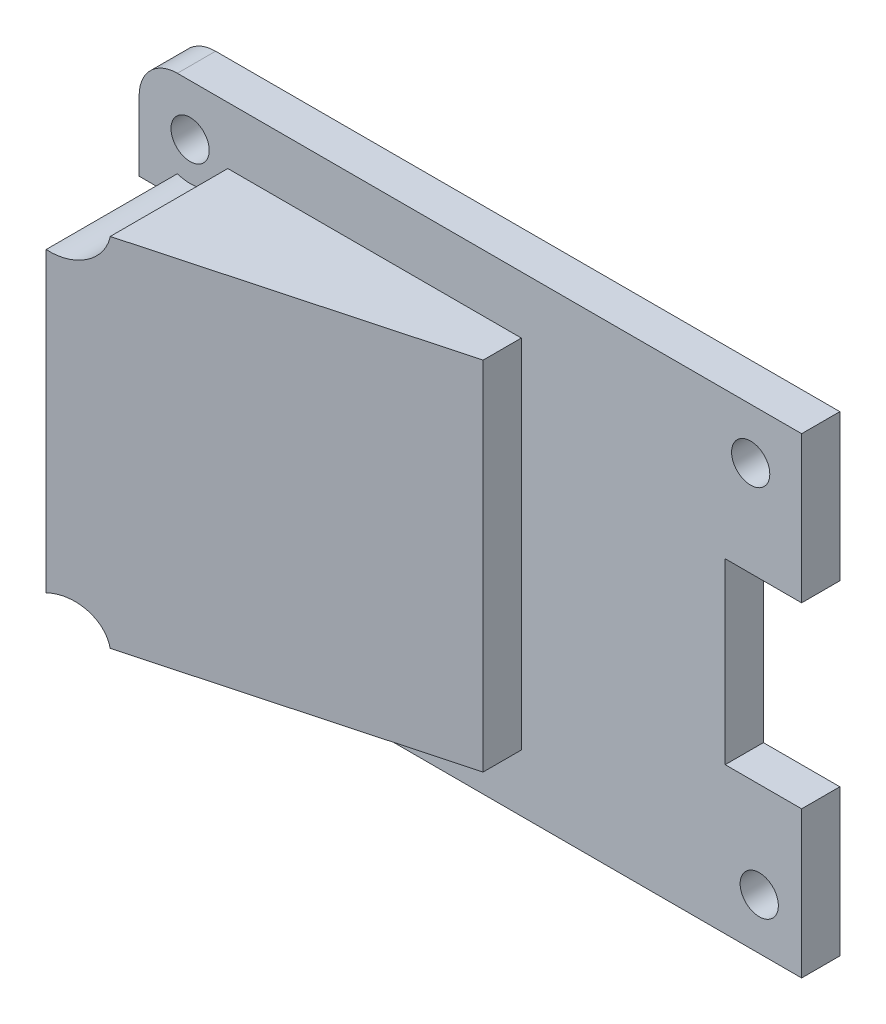
SolidWorks part; units mm, degrees
ref_plane "Alzado" through (0, 0, 0) normal (0, 0, 1) x (1, 0, 0)
ref_plane "Planta" through (0, 0, 0) normal (0, 1, 0) x (1, 0, 0)
ref_plane "Vista lateral" through (0, 0, 0) normal (1, 0, 0) x (0, 0, -1)
sketch "Croquis1" plane through (0, 0, 0) normal (0, 0, 1) x (1, 0, 0)
  line L1 (-65.2968, 25.2877) -> (-13.2968, 25.2877)
  line L2 (-65.2968, 25.2877) -> (-65.2968, -11.7123)
  line L3 (-65.2968, -11.7123) -> (-13.2968, -11.7123)
  line L4 (-13.2968, 25.2877) -> (-13.2968, -11.7123)
  dimension "D1" = 52
  dimension "D2" = 37
extrude "Saliente-Extruir1" add sketch "Croquis1" along normal blind 3
fillet "Redondeo1" radius 3 2 edges at (-65.2968, -11.7123, 1.5) (-65.2968, 25.2877, 1.5)
sketch "Croquis2" plane through (0, 0, 3) normal (0, 0, 1) x (1, 0, 0)
  line L0 (-62.2968, -11.7123) -> (-13.2968, -11.7123) construction
  line L3 (-65.2968, 22.2877) -> (-65.2968, -8.7123) construction
  circle A0 centre (-61.2968, 21.2877) radius 1.5
  circle A1 centre (-61.2968, -7.7123) radius 1.5
  circle A2 centre (-16.6241, -7.7123) radius 1.5
  circle A3 centre (-17.2968, 21.2877) radius 1.5
  dimension "D1" = 29
  dimension "D4" = 29
  dimension "D2" = 4
  dimension "D3" = 4
  dimension "D5" = 44
  dimension "D6" = 4
extrude "Cortar-Extruir1" cut sketch "Croquis2" against normal blind 3
sketch "Croquis3" plane through (0, 0, 3) normal (0, 0, 1) x (1, 0, 0)
  line L0 (-65.2968, 22.2877) -> (-65.2968, -8.7123) construction
  line L1 (-65.2968, 16.7877) -> (-36.2968, 16.7877)
  line L2 (-65.2968, 16.7877) -> (-65.2968, -3.2123)
  line L3 (-65.2968, -3.2123) -> (-36.2968, -3.2123)
  line L4 (-36.2968, 16.7877) -> (-36.2968, -3.2123)
  line L5 (-62.2968, -11.7123) -> (-13.2968, -11.7123) construction
  line L7 (-13.2968, -11.7123) -> (-13.2968, 25.2877) construction
  line L9 (-13.2968, 13.7877) -> (-19.2968, 13.7877)
  line L10 (-13.2968, 13.7877) -> (-13.2968, -0.2123)
  line L11 (-13.2968, -0.2123) -> (-19.2968, -0.2123)
  line L12 (-19.2968, 13.7877) -> (-19.2968, -0.2123)
  dimension "D1" = 29
  dimension "D2" = 20
  dimension "D3" = 8.5
  dimension "D4" = 6
  dimension "D5" = 14
  dimension "D6" = 11.5
extrude "Cortar-Extruir2" cut sketch "Croquis3" against normal blind 3
sketch "Croquis4" plane through (0, 0, 3) normal (0, 0, 1) x (1, 0, 0)
  line L0 (-57.2968, 16.7877) -> (-57.2968, 20.7902)
  line L1 (-36.2968, 16.7877) -> (-65.2968, 16.7877) construction
  line L2 (-57.2968, 20.7902) -> (-26.2968, 20.7902)
  line L3 (-26.2968, 20.7902) -> (-26.2968, -7.2123)
  line L4 (-26.2968, -7.2123) -> (-57.2968, -7.2123)
  line L5 (-57.2968, -7.2123) -> (-57.2968, -3.2123)
  line L6 (-65.2968, -3.2123) -> (-36.2968, -3.2123) construction
  line L7 (-57.2968, -3.2123) -> (-36.2968, -3.2123)
  line L8 (-36.2968, -3.2123) -> (-36.2968, 16.7877)
  line L9 (-36.2968, 16.7877) -> (-57.2968, 16.7877)
  line L10 (-65.2968, 22.2877) -> (-65.2968, 16.7877) construction
  line L11 (-65.2968, -3.2123) -> (-65.2968, -8.7123) construction
  dimension "D1" = 4
  dimension "D2" = 10
  dimension "D3" = 4.0026
  dimension "D4" = 8
  dimension "D5" = 8
extrude "Saliente-Extruir2" add sketch "Croquis4" along normal blind 9
sketch "Croquis5" plane through (0, 0, 12) normal (0, 0, 1) x (1, 0, 0)
  line L1 (-26.2968, 20.7902) -> (-62.2968, 20.7902)
  line L2 (-26.2968, 20.7902) -> (-26.2968, -7.2123)
  line L3 (-26.2968, -7.2123) -> (-62.2968, -7.2123)
  line L4 (-62.2968, 20.7902) -> (-62.2968, -7.2123)
  dimension "D1" = 28.0026
  dimension "D2" = 36
extrude "Saliente-Extruir3" add sketch "Croquis5" along normal blind 10.3
sketch "Croquis6" plane through (0, -7.2123, 0) normal (0, -1, 0) x (1, 0, 0)
  line L0 (-35.2968, 15) -> (-35.2968, 12.9954)
  line L2 (-35.2968, 12.9954) -> (-26.2968, 12.9954)
  line L3 (-35.2968, 15) -> (-62.2968, 22.3)
  line L6 (-26.2968, 22.3) -> (-26.2968, 3) construction
  line L7 (-26.2968, 14.7574) -> (-26.2968, 22.3)
  line L8 (-26.2968, 22.3) -> (-62.2968, 22.3)
  line L9 (-26.2968, 12.9954) -> (-26.2968, 14.7574)
extrude "Cortar-Extruir3" cut sketch "Croquis6" against normal up to vertex
sketch "Croquis7" plane through (1.3749, 0, 5.0851) normal (0.261, 0, 0.9653) x (0.9653, 0, -0.261)
  line L0 (-65.9578, 6.7889) -> (-65.9578, -26.7111)
  line L1 (-65.9578, 20.7902) -> (-65.9578, -7.2123) construction
  line L2 (-65.9578, -26.7111) -> (-37.9578, -26.7111)
  line L3 (-37.9578, -26.7111) -> (-37.9578, 40.2889)
  line L4 (-37.9578, 40.2889) -> (-65.9578, 40.2889)
  line L5 (-65.9578, 40.2889) -> (-65.9578, 6.7889)
  dimension "D1" = 28
  dimension "D2" = 67
  dimension "D3" = 33.5
  dimension "D4" = 33.5
extrude "Saliente-Extruir4" add sketch "Croquis7" along normal blind 8.5
sketch "Croquis8" plane through (3.5933, 0, 13.2905) normal (0.261, 0, 0.9653) x (0.9653, 0, -0.261)
  line L0 (-65.9578, -26.7111) -> (-37.9578, -26.7111) construction
  line L1 (-62.9078, -23.6611) -> (-41.0078, -23.6611)
  line L2 (-62.9078, -23.6611) -> (-62.9078, 37.2389)
  line L3 (-62.9078, 37.2389) -> (-41.0078, 37.2389)
  line L4 (-41.0078, -23.6611) -> (-41.0078, 37.2389)
  line L5 (-37.9578, 40.2889) -> (-65.9578, 40.2889) construction
  line L6 (-65.9578, 40.2889) -> (-65.9578, -26.7111) construction
  line L7 (-37.9578, -26.7111) -> (-37.9578, 40.2889) construction
  dimension "D1" = 3.05
  dimension "D2" = 3.05
  dimension "D3" = 3.05
  dimension "D4" = 3.05
extrude "Cortar-Extruir4" cut sketch "Croquis8" against normal blind 5.5
sketch "Croquis10" plane through (0, 20.7902, 0) normal (0, 1, 0) x (1, 0, 0)
  line L0 (-62.2968, -22.3) -> (-35.2968, -15)
  line L1 (-35.2968, -15) -> (-35.2968, -12)
  line L2 (-35.2968, -12) -> (-62.2968, -19.3)
  line L3 (-62.2968, -22.3) -> (-62.2968, -12) construction
  line L4 (-62.2968, -19.3) -> (-62.2968, -22.3)
extrude "Cortar-Extruir5" cut sketch "Croquis10" against normal blind 9
sketch "Croquis12" plane through (0, 20.7902, 0) normal (0, 1, 0) x (1, 0, 0)
  line L0 (-26.2968, -12.9954) -> (-35.2968, -12.9954)
  line L1 (-26.2968, -12.9954) -> (-26.2968, -11.4245)
  line L2 (-26.2968, -12.9954) -> (-26.2968, -3) construction
  line L4 (-26.2968, -11.4245) -> (-35.2968, -11.4245)
  line L5 (-35.2968, -11.4245) -> (-35.2968, -12.9954)
extrude "Cortar-Extruir6" cut sketch "Croquis12" against normal up to vertex
sketch "Croquis13" plane through (3.5933, 0, 13.2905) normal (0.261, 0, 0.9653) x (0.9653, 0, -0.261)
  line L0 (-37.9578, 40.2889) -> (-65.9578, 40.2889) construction
  line L1 (-37.9578, -26.7111) -> (-40.9578, -26.7111)
  line L2 (-37.9578, -26.7111) -> (-37.9578, 40.2889)
  line L3 (-37.9578, 40.2889) -> (-40.9578, 40.2889)
  line L4 (-40.9578, -26.7111) -> (-40.9578, 40.2889)
extrude "Saliente-Extruir5" add sketch "Croquis13" along normal blind 12
sketch "Croquis14" plane through (0, -7.2123, 0) normal (0, -1, 0) x (1, 0, 0)
  line L1 (-57.2968, 12) -> (-26.2968, 12)
  line L2 (-57.2968, 12) -> (-57.2968, 3)
  line L3 (-57.2968, 3) -> (-26.2968, 3)
  line L4 (-26.2968, 12) -> (-26.2968, 3)
extrude "Cortar-Extruir7" cut sketch "Croquis14" against normal up to vertex
sketch "Croquis17" plane through (0, 0, 3) normal (0, 0, 1) x (1, 0, 0)
  line L0 (-13.2968, -0.2123) -> (-19.2968, -0.2123)
  line L1 (-19.2968, -0.2123) -> (-19.2968, 13.7877)
  line L2 (-19.2968, 13.7877) -> (-13.2968, 13.7877)
  line L3 (-13.2968, 13.7877) -> (-13.2968, 25.2877)
  line L4 (-13.2968, 25.2877) -> (-62.2968, 25.2877)
  line L5 (-65.2968, 22.2877) -> (-65.2968, 16.7877)
  line L7 (-65.2968, 16.7877) -> (-36.2968, 16.7877)
  line L8 (-36.2968, 16.7877) -> (-36.2968, -3.2123)
  line L9 (-36.2968, -3.2123) -> (-65.2968, -3.2123)
  line L10 (-65.2968, -3.2123) -> (-65.2968, -8.7123)
  line L11 (-62.2968, -11.7123) -> (-13.2968, -11.7123)
  line L12 (-13.2968, -11.7123) -> (-13.2968, -0.2123)
  arc A0 (-62.2968, -11.7123) -> (-65.2968, -8.7123) centre (-62.2968, -8.7123) cw
  arc A1 (-65.2968, 22.2877) -> (-62.2968, 25.2877) centre (-62.2968, 22.2877) cw
  circle A2 centre (-61.2968, 21.2877) radius 1.5
  circle A3 centre (-61.2968, -7.7123) radius 1.5
  circle A4 centre (-16.6241, -7.7123) radius 1.5
  circle A5 centre (-17.2968, 21.2877) radius 1.5
extrude "Saliente-Extruir6" add sketch "Croquis17" along normal up to vertex (9 mm away)
sketch "Croquis18" plane through (0, -11.7123, 0) normal (0, -1, 0) x (1, 0, 0)
  line L1 (-13.2968, 0) -> (-67.494, 0)
  line L2 (-13.2968, 0) -> (-13.2968, 9)
  line L3 (-13.2968, 9) -> (-67.494, 9)
  line L4 (-67.494, 0) -> (-67.494, 9)
  dimension "D1" = 9
extrude "Cortar-Extruir8" cut sketch "Croquis18" against normal up to vertex
sketch "Croquis19" plane through (0, 0, 9) normal (0, 0, -1) x (-1, 0, 0)
  circle A0 centre (61.2968, 21.2877) radius 1.5
  circle A1 centre (61.2968, -7.7123) radius 1.5
extrude "Cortar-Extruir9" cut sketch "Croquis19" against normal up to vertex
sketch "Croquis20" plane through (1.3749, 0, 5.0851) normal (-0.261, 0, -0.9653) x (-0.9653, 0, 0.261)
  line L0 (37.9578, -26.7111) -> (37.9578, 40.2889) construction
  line L1 (65.9578, 40.2889) -> (37.9578, 40.2889)
  line L2 (65.9578, 40.2889) -> (65.9578, 34.2889)
  line L3 (65.9578, 34.2889) -> (37.9578, 34.2889)
  line L4 (37.9578, 40.2889) -> (37.9578, 34.2889)
  dimension "D1" = 6
extrude "Saliente-Extruir7" add sketch "Croquis20" along normal blind 3
sketch "Croquis21" plane through (0, 0, 9) normal (0, 0, -1) x (-1, 0, 0)
  line L0 (65.2968, 16.7877) -> (36.2968, 16.7877) construction
  line L1 (55.2968, 16.7877) -> (35.2968, 16.7877)
  line L2 (55.2968, 16.7877) -> (55.2968, 21.2877)
  line L3 (55.2968, 21.2877) -> (35.2968, 21.2877)
  line L4 (35.2968, 16.7877) -> (35.2968, 21.2877)
  line L5 (36.2968, -3.2123) -> (65.2968, -3.2123) construction
  line L6 (55.2968, -3.2123) -> (35.2968, -3.2123)
  line L7 (55.2968, -3.2123) -> (55.2968, -7.7123)
  line L8 (55.2968, -7.7123) -> (35.2968, -7.7123)
  line L9 (35.2968, -3.2123) -> (35.2968, -7.7123)
  line L10 (13.2968, 25.2877) -> (62.2968, 25.2877) construction
  line L11 (13.2968, -11.7123) -> (62.2968, -11.7123) construction
  line L12 (65.2968, 22.2877) -> (65.2968, 16.7877) construction
  line L13 (65.2968, -3.2123) -> (65.2968, -8.7123) construction
  dimension "D1" = 4
  dimension "D2" = 4
  dimension "D3" = 10
  dimension "D4" = 10
  dimension "D5" = 20
  dimension "D6" = 20
extrude "Cortar-Extruir10" cut sketch "Croquis21" against normal blind 2
sketch "Croquis22" plane through (0, 0, 12) normal (0, 0, 1) x (1, 0, 0)
  circle A0 centre (-61.2968, 21.2877) radius 3
  circle A1 centre (-61.2968, -7.7123) radius 3
extrude "Cortar-Extruir11" cut sketch "Croquis22" along normal up to vertex (10.3 mm away)
sketch "Croquis23" plane through (0, 0, 12) normal (0, 0, 1) x (1, 0, 0)
  circle A0 centre (-61.2968, 21.2877) radius 2
  circle A1 centre (-61.2968, -7.7123) radius 2
extrude "Cortar-Extruir12" cut sketch "Croquis23" along normal up to vertex
sketch "Croquis24" plane through (1.3749, 0, 5.0851) normal (-0.261, 0, -0.9653) x (-0.9653, 0, 0.261)
  line L1 (37.9578, -26.7111) -> (69.5992, -26.7111)
  line L2 (37.9578, -26.7111) -> (37.9578, 48.9096)
  line L3 (37.9578, 48.9096) -> (69.5992, 48.9096)
  line L4 (69.5992, -26.7111) -> (69.5992, 48.9096)
extrude "Cortar-Extruir13" cut sketch "Croquis24" against normal up to vertex
sketch "Croquis25" plane through (0.5919, 0, 2.1891) normal (-0.261, 0, -0.9653) x (-0.9653, 0, 0.261)
  line L1 (65.9578, 40.2889) -> (37.9578, 40.2889)
  line L2 (65.9578, 40.2889) -> (65.9578, 34.2889)
  line L3 (65.9578, 34.2889) -> (37.9578, 34.2889)
  line L4 (37.9578, 40.2889) -> (37.9578, 34.2889)
extrude "Cortar-Extruir14" cut sketch "Croquis25" against normal blind 10
sketch "Croquis27" plane through (0, 11.7902, 0) normal (0, 1, 0) x (1, 0, 0)
  line L0 (-35.2968, -12) -> (-35.2968, -15)
  line L1 (-35.2968, -15) -> (-62.2968, -22.3)
  line L2 (-62.2968, -22.3) -> (-62.2968, -19.3)
  line L3 (-62.2968, -19.3) -> (-35.2968, -12)
extrude "Saliente-Extruir8" add sketch "Croquis27" along normal up to vertex
sketch "Croquis30" plane through (0, 0, 12) normal (0, 0, 1) x (1, 0, 0)
  circle A0 centre (-61.2968, 21.2877) radius 3
extrude "Cortar-Extruir16" cut sketch "Croquis30" along normal up to vertex up to point (-62.2968, -4.8839, 22.3)
